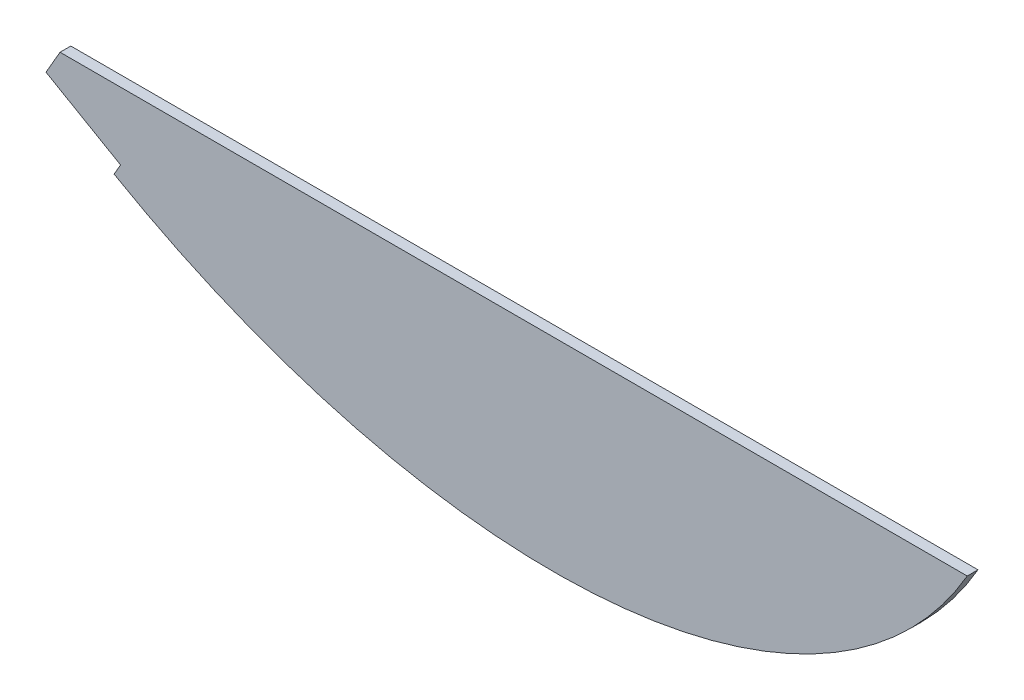
SolidWorks part; units mm, degrees
material "Plain Carbon Steel"
ref_plane "Front Plane" through (0, 0, 0) normal (0, 0, 1) x (1, 0, 0)
ref_plane "Top Plane" through (0, 0, 0) normal (0, 1, 0) x (1, 0, 0)
ref_plane "Right Plane" through (0, 0, 0) normal (1, 0, 0) x (0, 0, -1)
sketch "Sketch1" plane through (0, 0, 0) normal (0, 0, 1) x (1, 0, 0)
  line L1 (-99.8406, -66.9103) -> (128.8009, -66.9103)
  line L3 (-263.0057, 33.0897) -> (186.5359, 33.0897)
  line L5 (-263.0057, 33.0897) -> (-265.5157, 28.7422)
  line L6 (-265.5157, 28.7422) -> (-99.8406, -66.9103)
  line L8 (11.405, 33.0897) -> (-11.3675, -66.9103) construction
  line L9 (186.5359, 33.0897) -> (128.8009, -66.9103)
  point P1 (0, 0)
  dimension "D3" = 145
  dimension "D1" = 35
  dimension "D2" = 244.3144
  dimension "D6" = 100
  dimension "D8" = 5.02
  dimension "D9" = 30
  dimension "D10" = 60
extrude "Boss-Extrude1" add sketch "Sketch1" along normal blind 5
sketch "Sketch3" plane through (0, 0, 0) normal (0, 0, 1) x (1, 0, 0)
  line L0 (-209.8389, -3.4028) -> (-265.5157, 28.7422)
  line L1 (-209.8389, -3.4028) -> (-206.8389, 1.7934)
  line L2 (-265.5157, 28.7422) -> (-262.5157, 33.9384)
  line L3 (-206.8389, 1.7934) -> (-262.5157, 33.9384)
  line L4 (-263.0057, 33.0897) -> (-265.5157, 28.7422) construction
  dimension "D1" = 6
  dimension "D2" = 64.29
extrude "Cut-Extrude2" cut sketch "Sketch3" along normal through all
sketch "Sketch4" plane through (-50.9332, -88.2189, 0) normal (-0.5, -0.866, 0) x (0.866, -0.5, 0)
  line L0 (-180.0244, 5) -> (-242.617, 5) construction
  line L1 (-242.617, 5) -> (-242.617, 0) construction
  line L2 (-180.0244, 5) -> (-180.0244, 0) construction
  line L3 (-260.0244, -35) -> (-124.2928, 100.7316) construction
  line L4 (55, 0) -> (-55, 0) construction
  line L5 (-180.0244, 0) -> (-242.617, 0) construction
  line L6 (-242.617, 5) -> (-220.0244, 5)
  line L7 (-242.617, 5) -> (-242.617, 0)
  line L8 (-242.617, 0) -> (-220.0244, 0)
  line L9 (-220.0244, 5) -> (-220.0244, 0)
  line L10 (-255.4916, -34.7098) -> (-177.7177, 43.0641) construction
  line L11 (-180.0244, 5) -> (-242.617, 5) construction
  circle A0 centre (-260.0244, -35) radius 80 construction
  point P20 (0, 0)
  dimension "D1" = 160
  dimension "D2" = 40
  dimension "D3" = 45
  dimension "D4" = 3
extrude "Cut-Extrude3" cut sketch "Sketch4" against normal up to next
sketch "Sketch5" plane through (0, 0, 0) normal (0, 0, 1) x (1, 0, 0)
  line L3 (-209.8389, -3.4028) -> (-99.8406, -66.9103) construction
  line L4 (-209.8389, -3.4028) -> (71.6405, -165.915)
  line L6 (71.6405, -165.915) -> (186.5359, 33.0897)
  line L8 (128.8009, -66.9103) -> (186.5359, 33.0897) construction
  line L9 (186.5359, 33.0897) -> (-234.958, 33.0897) construction
  ellipse E0 centre (-94.9435, 195.6019) end of major axis (186.5359, 33.0897) minor radius 229.7908 (-209.8389, -3.4028) -> (186.5359, 33.0897) ccw
  point P2 (0, 0)
  point P14 (0, 0)
  point P17 (0, 0)
extrude "Cut-Extrude4" cut sketch "Sketch5" along normal through all
